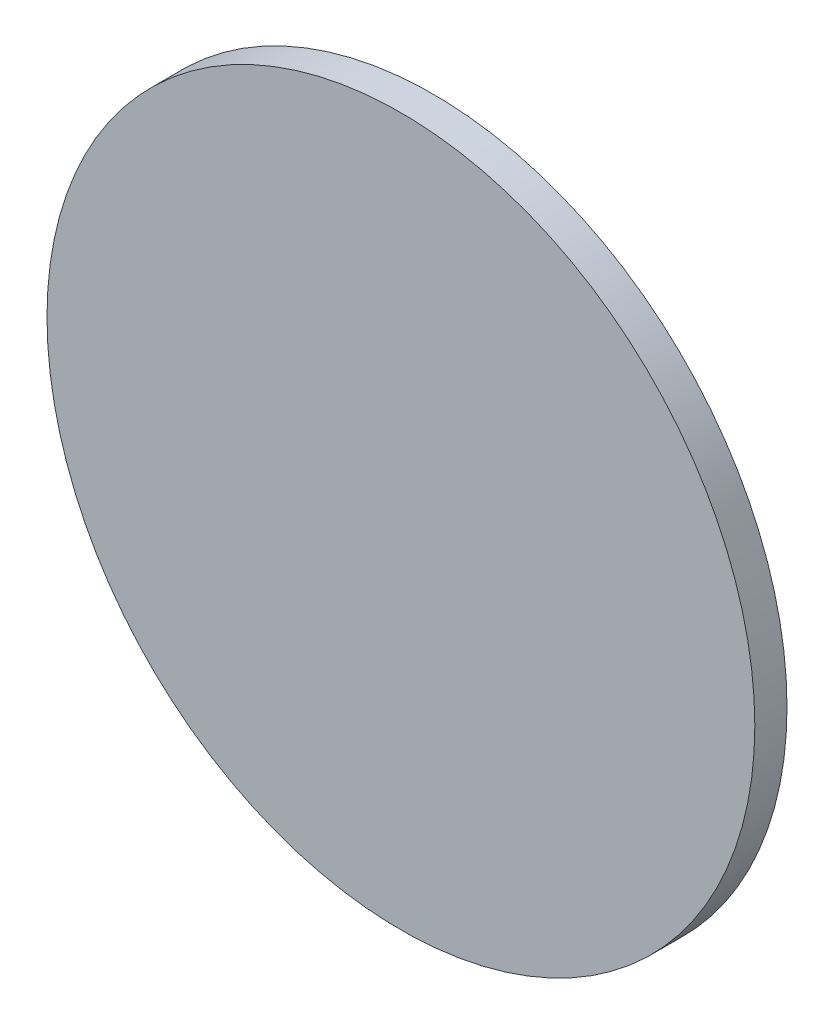
SolidWorks part; units mm, degrees
ref_plane "Alzado" through (0, 0, 0) normal (0, 0, 1) x (1, 0, 0)
ref_plane "Planta" through (0, 0, 0) normal (0, 1, 0) x (1, 0, 0)
ref_plane "Vista lateral" through (0, 0, 0) normal (1, 0, 0) x (0, 0, -1)
sketch "Croquis1" plane through (0, 0, 0) normal (0, 0, 1) x (1, 0, 0)
  circle A0 centre (0, 0) radius 33
extrude "Saliente-Extruir1" add sketch "Croquis1" along normal blind 3
